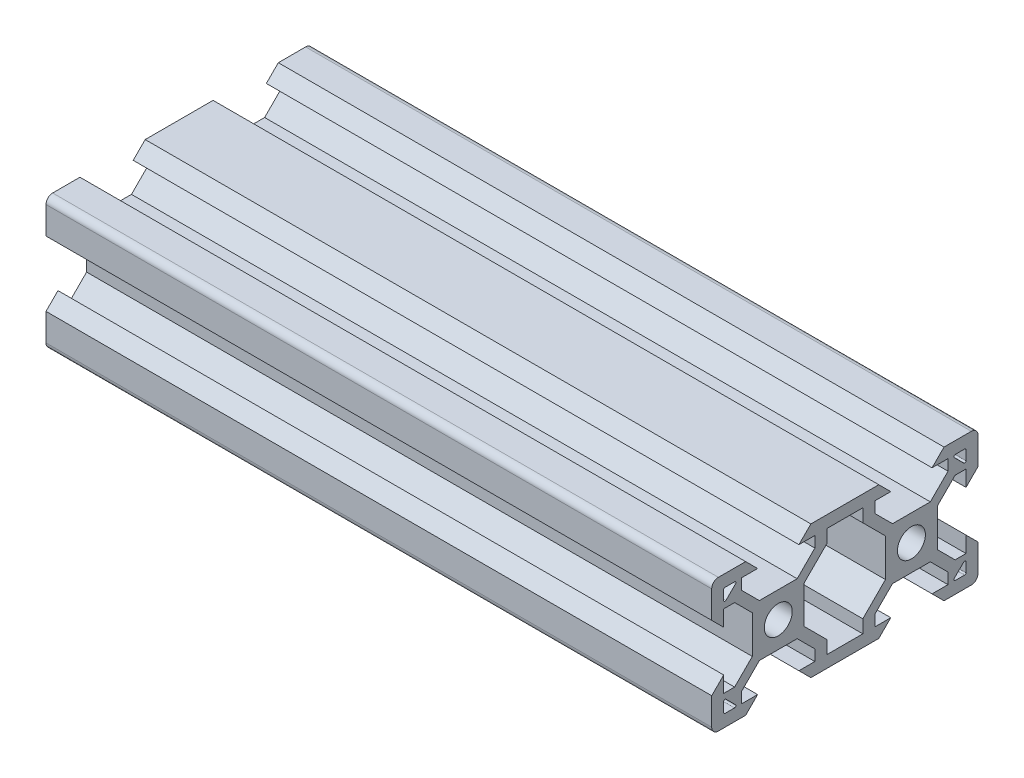
SolidWorks part; units mm, degrees
material "1060 Alloy"
ref_plane "Front Plane" through (0, 0, 0) normal (0, 0, 1) x (1, 0, 0)
ref_plane "Top Plane" through (0, 0, 0) normal (0, 1, 0) x (1, 0, 0)
ref_plane "Right Plane" through (0, 0, 0) normal (1, 0, 0) x (0, 0, -1)
sketch "Sketch4" plane through (0, 0, 0) normal (1, 0, 0) x (0, 0, -1)
  line L0 (-19.2399, 7.0114) -> (20.7601, 7.0114) construction
  dimension "D1" = 40
sketch "Sketch5" plane through (0, 0, 0) normal (1, 0, 0) x (0, 0, -1)
  line L0 (-19.998, 4.9) -> (-18.198, 3.1)
  line L1 (-18.198, 3.1) -> (-18.198, 5.4993)
  line L2 (-18.198, 5.4993) -> (-16.558, 5.4993)
  line L3 (-16.558, 5.4993) -> (-13.9, 2.8413)
  line L4 (-13.9, 2.8413) -> (-13.9, -2.8387)
  line L5 (-13.9, -2.8387) -> (-16.558, -5.4967)
  line L6 (-16.558, -5.4967) -> (-18.198, -5.4967)
  line L7 (-18.198, -5.4967) -> (-18.198, -3.1)
  line L8 (-18.198, -3.1) -> (-19.998, -4.9)
  line L9 (-19.998, -4.9) -> (-19.998, -9)
  line L10 (-18.998, -10) -> (-14.9, -10)
  line L11 (-14.9, -10) -> (-13.1, -8.2)
  line L12 (-13.1, -8.2) -> (-15.5, -8.2)
  line L13 (-15.5, -8.2) -> (-15.5, -6.56)
  line L14 (-15.5, -6.56) -> (-12.84, -3.9)
  line L15 (-12.84, -3.9) -> (-7.16, -3.9)
  line L16 (-7.16, -3.9) -> (-4.5, -6.56)
  line L17 (-4.5, -6.56) -> (-4.5, -8.2)
  line L18 (-4.5, -8.2) -> (-6.9, -8.2)
  line L19 (-6.9, -8.2) -> (-5.1, -10)
  line L20 (-5.1, -10) -> (5.1, -10)
  line L21 (5.1, -10) -> (6.9, -8.2)
  line L22 (6.9, -8.2) -> (4.496, -8.2)
  line L23 (4.496, -8.2) -> (4.496, -6.56)
  line L24 (4.496, -6.56) -> (7.156, -3.9)
  line L25 (7.156, -3.9) -> (12.836, -3.9)
  line L26 (12.836, -3.9) -> (15.496, -6.56)
  line L27 (15.496, -6.56) -> (15.496, -8.2)
  line L28 (15.496, -8.2) -> (13.1, -8.2)
  line L29 (13.1, -8.2) -> (14.9, -10)
  line L30 (14.9, -10) -> (19.002, -10)
  line L31 (20.002, -9) -> (20.002, -4.9)
  line L32 (20.002, -4.9) -> (18.202, -3.1)
  line L33 (18.202, -3.1) -> (18.202, -5.5046)
  line L34 (18.202, -5.5046) -> (16.562, -5.5046)
  line L35 (16.562, -5.5046) -> (13.9, -2.8426)
  line L36 (13.9, -2.8426) -> (13.9, 2.8374)
  line L37 (13.9, 2.8374) -> (16.562, 5.4993)
  line L38 (16.562, 5.4993) -> (18.202, 5.4993)
  line L39 (18.202, 5.4993) -> (18.202, 3.1)
  line L40 (18.202, 3.1) -> (20.002, 4.9)
  line L41 (20.002, 4.9) -> (20.002, 9)
  line L42 (19.002, 10) -> (14.9, 10)
  line L43 (14.9, 10) -> (13.1, 8.2)
  line L44 (13.1, 8.2) -> (15.5013, 8.2)
  line L45 (15.5013, 8.2) -> (15.5013, 6.56)
  line L46 (15.5013, 6.56) -> (12.8413, 3.9)
  line L47 (12.8413, 3.9) -> (7.1613, 3.9)
  line L48 (7.1613, 3.9) -> (4.5013, 6.56)
  line L49 (4.5013, 6.56) -> (4.5013, 8.2)
  line L50 (4.5013, 8.2) -> (6.9, 8.2)
  line L51 (6.9, 8.2) -> (5.1, 10)
  line L52 (5.1, 10) -> (-5.1, 10)
  line L53 (-5.1, 10) -> (-6.9, 8.2)
  line L54 (-6.9, 8.2) -> (-4.5013, 8.2)
  line L55 (-4.5013, 8.2) -> (-4.5013, 6.56)
  line L56 (-4.5013, 6.56) -> (-7.1613, 3.9)
  line L57 (-7.1613, 3.9) -> (-12.8413, 3.9)
  line L58 (-12.8413, 3.9) -> (-15.5013, 6.56)
  line L59 (-15.5013, 6.56) -> (-15.5013, 8.2)
  line L60 (-15.5013, 8.2) -> (-13.1, 8.2)
  line L61 (-13.1, 8.2) -> (-14.9, 10)
  line L62 (-14.9, 10) -> (-18.998, 10)
  line L63 (-19.998, 9) -> (-19.998, 4.9)
  line L64 (6.1, -2.84) -> (6.1, 2.84)
  line L65 (6.1, 2.84) -> (2.7, 6.24)
  line L66 (2.7, 6.24) -> (2.7, 8.2)
  line L67 (2.7, 8.2) -> (-2.7, 8.2)
  line L68 (-2.7, 8.2) -> (-2.7, 6.24)
  line L69 (-2.7, 6.24) -> (-6.1, 2.84)
  line L70 (-6.1, 2.84) -> (-6.1, -2.84)
  line L71 (-6.1, -2.84) -> (-2.7, -6.24)
  line L72 (-2.7, -6.24) -> (-2.7, -8.2)
  line L73 (-2.7, -8.2) -> (2.7, -8.2)
  line L74 (2.7, -8.2) -> (2.7, -6.24)
  line L75 (2.7, -6.24) -> (6.1, -2.84)
  line L76 (0, -8.2) -> (0, 8.2) construction
  line L77 (6.1, 0) -> (-6.1, 0) construction
  line L78 (16.562, 5.4993) -> (15.5013, 6.56) construction
  line L79 (16.5713, 8.2) -> (18.002, 8.2)
  line L81 (17.8606, 6.4279) -> (16.4299, 7.8586)
  line L82 (18.202, 8) -> (18.202, 6.5693)
  line L83 (18.002, 6.5693) -> (18.002, 8) construction
  line L84 (18.002, 8) -> (16.5713, 8) construction
  line L85 (16.5713, 8) -> (18.002, 6.5693) construction
  line L86 (16.5713, -8.2) -> (18.002, -8.2)
  line L87 (18.202, -8) -> (18.202, -6.5693)
  line L88 (17.8606, -6.4279) -> (16.4299, -7.8586)
  line L89 (-17.8606, 6.4279) -> (-16.4299, 7.8586)
  line L90 (-16.5713, 8.2) -> (-18.002, 8.2)
  line L91 (-18.202, 8) -> (-18.202, 6.5693)
  line L92 (-16.5713, -8.2) -> (-18.002, -8.2)
  line L93 (-17.8606, -6.4279) -> (-16.4299, -7.8586)
  line L94 (-18.202, -8) -> (-18.202, -6.5693)
  circle A0 centre (-10, 0) radius 2.1
  circle A1 centre (10, 0) radius 2.1
  arc A2 (-19.998, -9) -> (-18.998, -10) centre (-18.998, -9) ccw
  arc A5 (-18.998, 10) -> (-19.998, 9) centre (-18.998, 9) ccw
  arc A6 (20.002, -9) -> (19.002, -10) centre (19.002, -9) cw
  arc A7 (20.002, 9) -> (19.002, 10) centre (19.002, 9) ccw
  arc A8 (18.002, 8.2) -> (18.202, 8) centre (18.002, 8) cw
  arc A10 (16.4299, 7.8586) -> (16.5713, 8.2) centre (16.5713, 8) cw
  arc A12 (18.202, 6.5693) -> (17.8606, 6.4279) centre (18.002, 6.5693) cw
  arc A13 (16.4299, -7.8586) -> (16.5713, -8.2) centre (16.5713, -8) ccw
  arc A14 (18.002, -8.2) -> (18.202, -8) centre (18.002, -8) ccw
  arc A15 (18.202, -6.5693) -> (17.8606, -6.4279) centre (18.002, -6.5693) ccw
  arc A16 (-18.202, 6.5693) -> (-17.8606, 6.4279) centre (-18.002, 6.5693) ccw
  arc A17 (-16.4299, 7.8586) -> (-16.5713, 8.2) centre (-16.5713, 8) ccw
  arc A18 (-18.002, 8.2) -> (-18.202, 8) centre (-18.002, 8) ccw
  arc A19 (-18.002, -8.2) -> (-18.202, -8) centre (-18.002, -8) cw
  arc A20 (-16.4299, -7.8586) -> (-16.5713, -8.2) centre (-16.5713, -8) cw
  arc A21 (-18.202, -6.5693) -> (-17.8606, -6.4279) centre (-18.002, -6.5693) cw
  dimension "D1" = 4.2
  dimension "D20" = 3.9
  dimension "D27" = 1
  dimension "D40" = 1
  dimension "D41" = 1
  dimension "D42" = 1
  dimension "D45" = 0.2
  dimension "D47" = 1.07
  dimension "D48" = 1.07
  dimension "D49" = 0.2
  dimension "D2" = 20
  dimension "D3" = 10
  dimension "D4" = 5.68
  dimension "D5" = 5.4
  dimension "D6" = 1.96
  dimension "D7" = 45
  dimension "D8" = 1.8
  dimension "D9" = 1.64
  dimension "D10" = 1.8
  dimension "D11" = 40
  dimension "D12" = 20
  dimension "D13" = 3.9
  dimension "D14" = 1.5
  dimension "D15" = 1.5
  dimension "D16" = 3.9
  dimension "D17" = 3.9
  dimension "D18" = 3.9
  dimension "D19" = 3.9
  dimension "D21" = 1.5
  dimension "D22" = 1.5
  dimension "D23" = 1.64
  dimension "D24" = 45
  dimension "D25" = 1.5
  dimension "D26" = 1.8
  dimension "D28" = 6.2
  dimension "D29" = 6.2
  dimension "D30" = 6.2
  dimension "D31" = 6.2
  dimension "D32" = 6.2
  dimension "D33" = 3.1
  dimension "D34" = 3.1
  dimension "D35" = 3.1
  dimension "D36" = 3.1
  dimension "D37" = 6.2
  dimension "D38" = 3.1
  dimension "D39" = 3.1
  dimension "D43" = 1.64
  dimension "D44" = 135
  dimension "D46" = 45
extrude "Boss-Extrude1" add sketch "Sketch5" along normal mid plane 100
